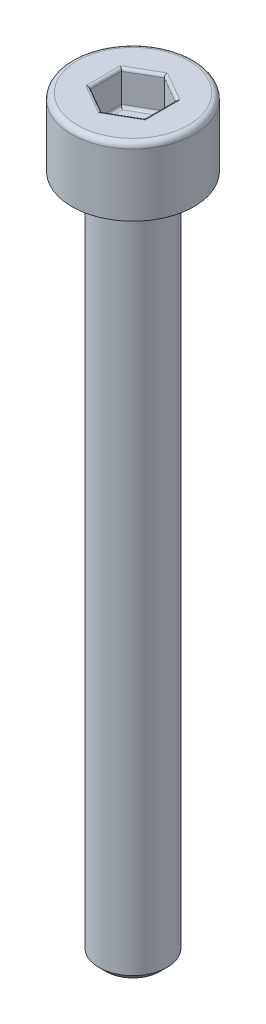
SolidWorks part; units mm, degrees
ref_plane "Front Plane" through (0, 0, 0) normal (0, 0, 1) x (1, 0, 0)
ref_plane "Top Plane" through (0, 0, 0) normal (0, 1, 0) x (1, 0, 0)
ref_plane "Right Plane" through (0, 0, 0) normal (1, 0, 0) x (0, 0, -1)
sketch "Sketch1" plane through (0, 0, 0) normal (0, 0, 1) x (1, 0, 0)
  line L0 (0, 0) -> (0, -47.0967) construction
  line L1 (0, -27.5) -> (-1.25, -27.5)
  line L2 (-1.25, -27.5) -> (-1.25, -2.5)
  line L3 (-1.25, -2.5) -> (-2.25, -2.5)
  line L4 (-2.25, -2.5) -> (-2.25, 0)
  line L5 (-2.25, 0) -> (0, 0)
  line L6 (0, 0) -> (0, -27.5)
  dimension "D1" = 25
  dimension "d" = 2.5
  dimension "k" = 2.5
  dimension "dk" = 4.5
revolve "Revolve1" add sketch "Sketch1" angle 360 about L0
chamfer "Chamfer1" distance 0.25 angle 45 2 edges at (0, -2.5, 1.25) (0, -27.5, 1.25)
fillet "Fillet1" radius 0.2 1 edges at (0, 0, 2.25)
sketch "Sketch2" plane through (0, 0, 0) normal (0, 1, 0) x (1, 0, 0)
  line L1 (0, 1.1547) -> (-1, 0.5774)
  line L2 (-1, 0.5774) -> (-1, -0.5774)
  line L3 (-1, -0.5774) -> (0, -1.1547)
  line L4 (0, -1.1547) -> (1, -0.5774)
  line L5 (1, -0.5774) -> (1, 0.5774)
  line L6 (1, 0.5774) -> (0, 1.1547)
  circle A0 centre (0, 0) radius 1 construction
  dimension "s" = 2
extrude "Cut-Extrude1" cut sketch "Sketch2" against normal blind 1.25
fillet "Fillet2" radius 0.1 12 edges at (-0.5, 0, -0.866) (-1, 0, 0) (-0.5, 0, 0.866) (0.5, 0, 0.866) (1, 0, 0) (0.5, 0, -0.866) (1, -1.25, 0) (0.5, -1.25, 0.866) (-0.5, -1.25, 0.866) (-1, -1.25, 0) (-0.5, -1.25, -0.866) (0.5, -1.25, -0.866)
